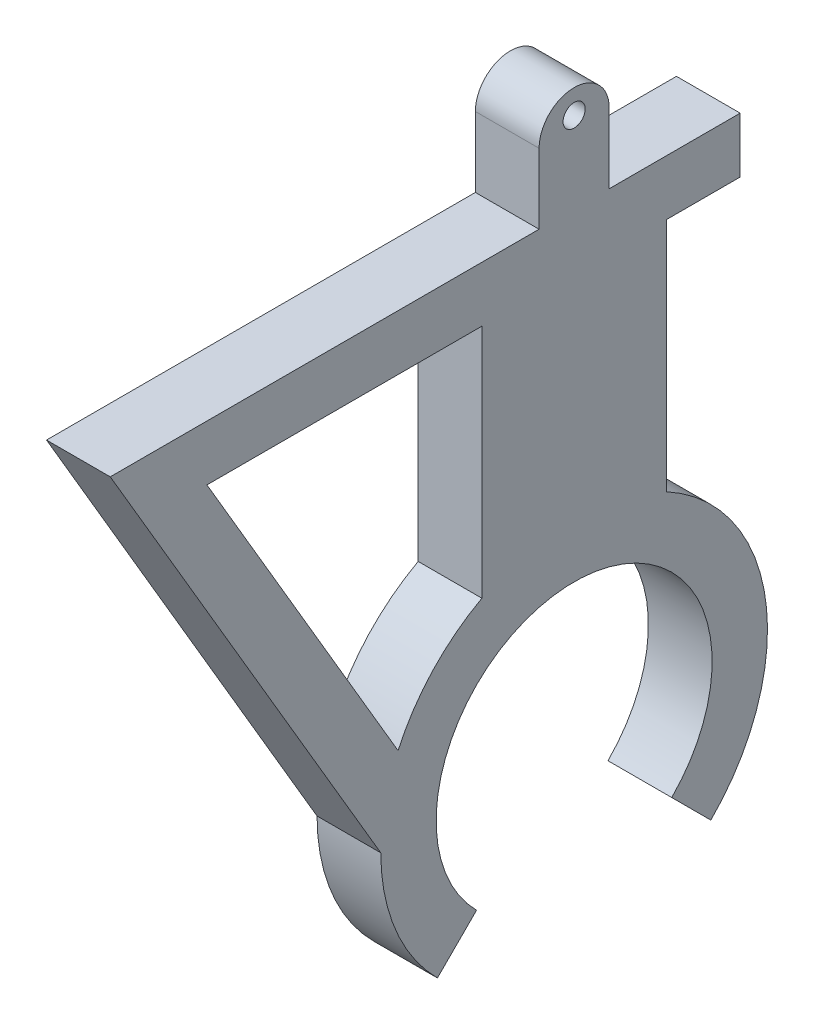
SolidWorks part; units mm, degrees
ref_plane "Front Plane" through (0, 0, 0) normal (0, 0, 1) x (1, 0, 0)
ref_plane "Top Plane" through (0, 0, 0) normal (0, 1, 0) x (1, 0, 0)
ref_plane "Right Plane" through (0, 0, 0) normal (1, 0, 0) x (0, 0, -1)
sketch "Sketch1" plane through (0, 0, 0) normal (1, 0, 0) x (0, 0, -1)
  line L0 (-2.6446, -2.6446) -> (2.6446, -2.6446) construction
  line L1 (-2.6446, -2.6446) -> (-3.7052, -3.7052)
  line L2 (3.7052, -3.7052) -> (2.6446, -2.6446)
  line L3 (0, 0) -> (0, 6.3411) construction
  line L4 (-2.5, 12.4907) -> (-0.95, 12.4907)
  line L5 (-2.5, 12.4907) -> (-2.5, 4.6052)
  line L6 (-0.95, 14.3907) -> (-0.95, 12.4907)
  line L7 (2.5, 12.4907) -> (2.5, 4.6052)
  line L8 (-2.5, 12.4907) -> (2.5, 4.6052) construction
  line L9 (-2.5, 4.6052) -> (2.5, 12.4907) construction
  line L10 (-0.95, 14.3907) -> (0.95, 14.3907) construction
  line L11 (0.95, 12.4907) -> (2.5, 12.4907)
  line L12 (0.95, 14.3907) -> (0.95, 12.4907)
  line L13 (-0.95, 14.3907) -> (0.95, 12.4907) construction
  line L14 (-0.95, 12.4907) -> (0.95, 14.3907) construction
  line L15 (-2.5, 12.4907) -> (-12.5716, 12.4907)
  line L16 (-12.5716, 12.4907) -> (-5.24, 0)
  line L17 (-2.5, 10.9907) -> (-9.9519, 10.9907)
  line L18 (-9.9519, 10.9907) -> (-4.7717, 2.1653)
  line L19 (-9.9519, 10.9907) -> (-3.9464, 0.7593) construction
  line L20 (-52.6576, 12.4907) -> (-57.4836, 12.4907) construction
  line L21 (2.5, 12.4907) -> (4.5, 12.4907)
  line L22 (2.5, 12.4907) -> (2.5, 10.9907)
  line L23 (2.5, 10.9907) -> (4.5, 10.9907)
  line L24 (4.5, 12.4907) -> (4.5, 10.9907)
  arc A0 (-2.6446, -2.6446) -> (2.6446, -2.6446) centre (0, 0) cw
  arc A1 (-3.7052, -3.7052) -> (-2.5, 4.6052) centre (0, 0) cw
  arc A2 (2.5, 4.6052) -> (3.7052, -3.7052) centre (0, 0) cw
  arc A3 (-3.7052, -3.7052) -> (3.7052, -3.7052) centre (0, 0) cw construction
  arc A4 (-0.95, 14.3907) -> (0.95, 14.3907) centre (0, 14.3907) cw
  circle A5 centre (0, 14.6907) radius 0.3
  point P7 (0, 8.5479)
  point P12 (0, 3.74)
  point P16 (0, 14.3907)
  point P17 (0, 13.4407)
  dimension "D1" = 3.74
  dimension "D3" = 1.5
  dimension "D6" = 1.9
  dimension "D8" = 0.6
  dimension "D9" = 1.5
  dimension "D2" = 90
  dimension "D5" = 5
  dimension "D7" = 1.9
  dimension "D10" = 2
extrude "Boss-Extrude1" add sketch "Sketch1" along normal blind 1.7272 contours A4 L6 L4 L5 A1 L1 A0 L2 A2 L7 L11 L12 A5 | L16 A1 L18 L17 L5 L15 | L24 L21 L7 L23
